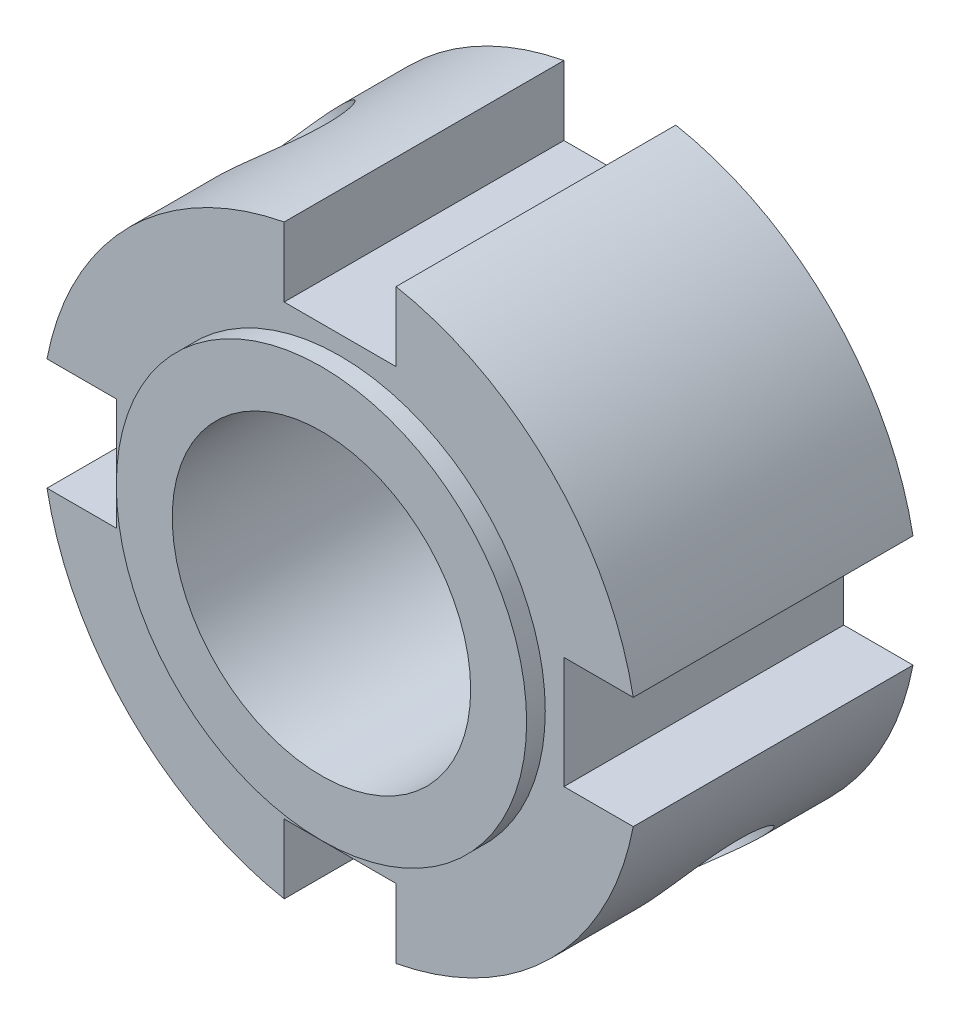
SolidWorks part; units mm, degrees
ref_plane "前视基准面" through (0, 0, 0) normal (0, 0, 1) x (1, 0, 0)
ref_plane "上视基准面" through (0, 0, 0) normal (0, 1, 0) x (1, 0, 0)
ref_plane "右视基准面" through (0, 0, 0) normal (1, 0, 0) x (0, 0, -1)
sketch "草图1" plane through (0, 0, 0) normal (0, 0, 1) x (1, 0, 0)
  circle A0 centre (0, 0) radius 8
  circle A1 centre (0, 0) radius 4
  dimension "D1" = 16
  dimension "D2" = 8
extrude "凸台-拉伸1" add sketch "草图1" along normal blind 7.5 from offset 3.5 offset against normal yes
cosmetic thread "装饰螺纹线1" parameters "D1"=6, "D2"=8.2
sketch "草图2" plane through (0, 0, 4) normal (0, 0, 1) x (1, 0, 0)
  circle A0 centre (0, 0) radius 4 construction
  circle A1 centre (0, 0) radius 4
  circle A2 centre (0, 0) radius 5.5
  dimension "D1" = 11
extrude "凸台-拉伸2" add sketch "草图2" along normal blind 0.5
sketch "草图3" plane through (0, 0, -3.5) normal (0, 0, -1) x (-1, 0, 0)
  line L0 (0, -9.7101) -> (0, 10.2953) construction
  line L1 (-9.1009, 0) -> (10.4979, 0) construction
  line L2 (-7.8581, -1.5) -> (-6, -1.5)
  line L3 (-7.8581, 1.5) -> (-6, 1.5)
  line L4 (1.5, -7.8581) -> (1.5, -6)
  line L5 (-1.5, -7.8581) -> (-1.5, -6)
  line L6 (-1.5, -9.7101) -> (-1.5, 10.2953) construction
  line L7 (1.5, -9.7101) -> (1.5, 10.2953) construction
  line L8 (-1.5, 6) -> (1.5, 6)
  line L9 (-1.5, -6) -> (1.5, -6)
  line L10 (-9.1009, -1.5) -> (10.4979, -1.5) construction
  line L11 (-9.1009, 1.5) -> (10.4979, 1.5) construction
  line L12 (-6, 1.5) -> (-6, -1.5)
  line L14 (6, -1.5) -> (7.8581, -1.5)
  line L15 (6, 1.5) -> (7.8581, 1.5)
  line L16 (-1.5, 6) -> (-1.5, 7.8581)
  line L17 (1.5, 6) -> (1.5, 7.8581)
  line L18 (6, 1.5) -> (6, -1.5)
  circle A1 centre (0, 0) radius 8 construction
  arc A2 (-1.5, -7.8581) -> (1.5, -7.8581) centre (0, 0) ccw
  arc A3 (7.8581, -1.5) -> (7.8581, 1.5) centre (0, 0) ccw
  arc A5 (-7.8581, 1.5) -> (-7.8581, -1.5) centre (0, 0) ccw
  arc A7 (1.5, 7.8581) -> (-1.5, 7.8581) centre (0, 0) ccw
  dimension "D1" = 12
  dimension "D6" = 12
  dimension "D2" = 1.5
  dimension "D3" = 1.5
  dimension "D4" = 1.5
  dimension "D5" = 1.5
extrude "切除-拉伸1" cut sketch "草图3" against normal up to surface (7.5 mm away) up to face at (8, 0, 4)
ref_plane "基准面1" through (5.6569, -5.6569, 0) normal (0.7071, -0.7071, 0) x (0, 0, -1)
sketch "草图5" plane through (5.6569, -5.6569, 0) normal (0.7071, -0.7071, 0) x (0, 0, -1)
  point P0 (0, 0)
hole_wizard "M4 螺纹孔1" positions "草图7" profile "草图6" tap size "M4" standard "Gb"
sketch "草图7" plane through (5.6569, -5.6569, 0) normal (0.7071, -0.7071, 0) x (0, 0, -1)
  point P0 (0, 0)
sketch "草图6" plane through (5.6569, -5.6569, 0) normal (0, 0, 1) x (0.7071, 0.7071, 0)
  line L0 (0, 0) -> (0, 18.4914)
  line L1 (0, 18.4914) -> (1.65, 17.5)
  line L2 (1.65, 17.5) -> (1.65, 0)
  line L5 (1.65, 0) -> (0, 0)
  line L10 (0, 18.4914) -> (-1.65, 17.5) construction
  line L11 (0, -6.35) -> (0, 107.95) construction
  dimension "螺纹孔钻头直径" = 3.3
  dimension "螺纹孔钻头深度" = 17.5
  dimension "导头角度" = 118
cosmetic thread "孔螺蚊线1" parameters "D1"=14, "D2"=4
